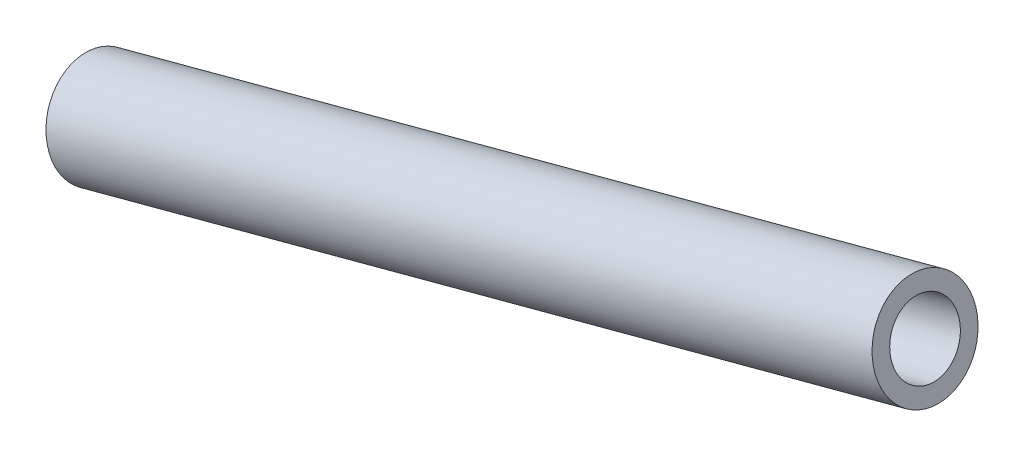
SolidWorks part; units mm, degrees
ref_plane "Front Plane" through (0, 0, 0) normal (0, 0, 1) x (1, 0, 0)
ref_plane "Top Plane" through (0, 0, 0) normal (0, 1, 0) x (1, 0, 0)
ref_plane "Right Plane" through (0, 0, 0) normal (1, 0, 0) x (0, 0, -1)
sketch "Sketch1" plane through (-33.0995, -8.869, 0) normal (-0.9659, -0.2588, 0) x (0, 0, 1)
  circle A0 centre (56.5779, -28.092) radius 3
  circle A1 centre (56.5779, -28.092) radius 2
  dimension "D1" = 6
  dimension "D2" = 4
extrude "Boss-Extrude1" add sketch "Sketch1" along normal blind 50
